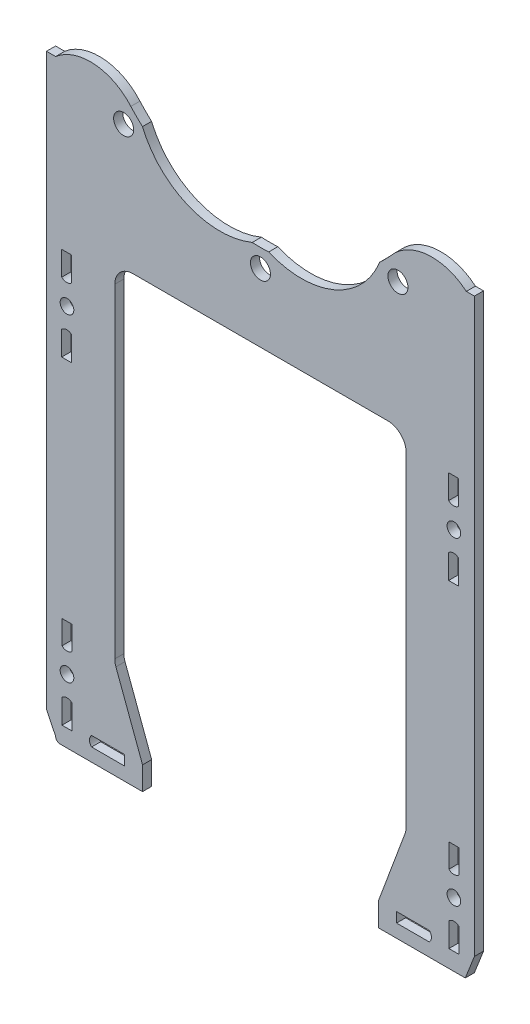
SolidWorks part; units mm, degrees
ref_plane "前视基准面" through (0, 0, 0) normal (0, 0, 1) x (1, 0, 0)
ref_plane "上视基准面" through (0, 0, 0) normal (0, 1, 0) x (1, 0, 0)
ref_plane "右视基准面" through (0, 0, 0) normal (1, 0, 0) x (0, 0, -1)
sketch "草图3" plane through (0, 0, 0) normal (0, 0, 1) x (1, 0, 0)
  line L0 (-37, -95.9902) -> (-37, -96.0902) construction
  line L5 (-37, -93.9902) -> (-30, -93.9902) construction
  line L6 (-37, -93.9902) -> (-37, -95.9902) construction
  line L7 (-37, -95.9902) -> (-30, -95.9902) construction
  line L8 (-30, -93.9902) -> (-30, -95.9902) construction
  line L9 (-37, -96.0902) -> (-37.1, -96.0902) construction
  line L12 (-42.5, -14.9402) -> (-41.8015, -14.9402) construction
  line L19 (-37.1, -96.0902) -> (-29.9, -96.0902)
  line L21 (-37.1, -93.8902) -> (-29.9, -93.8902)
  line L22 (-29.9, -96.0902) -> (-29.9, -93.8902)
  line L119 (-41.4551, -19.8902) -> (-41.4551, -25.1902)
  line L120 (-41.4551, -25.1902) -> (-43.6551, -25.1902)
  line L121 (-43.6551, -25.1902) -> (-43.6551, -19.8902)
  line L122 (-47, 31.3171) -> (-47, -93.8902)
  line L124 (37.1, -93.8902) -> (29.9, -93.8902)
  line L136 (37.1, -96.0902) -> (29.9, -96.0902)
  line L147 (30, -93.9902) -> (30, -95.9902) construction
  line L148 (29.9, -96.0902) -> (29.9, -93.8902)
  line L153 (37, -96.0902) -> (37.1, -96.0902) construction
  line L154 (37, -93.9902) -> (37, -95.9902) construction
  line L155 (37, -95.9902) -> (37, -96.0902) construction
  line L157 (43.5449, -25.1902) -> (43.5449, -19.8902)
  line L158 (41.3449, -25.1902) -> (43.5449, -25.1902)
  line L159 (41.3449, -19.8902) -> (41.3449, -25.1902)
  line L171 (-25.9, -97.9902) -> (-25.9, -93.8902)
  line L180 (0, 10.5098) -> (0, 13.5) construction
  line L187 (25.9, -97.9902) -> (25.9, -93.8902)
  line L195 (-25.9, -97.9902) -> (-25.9, -98.9902)
  line L196 (-25.9, -98.9902) -> (-45, -98.9902) construction
  line L197 (-45, -98.9902) -> (-45, -97.9902) construction
  line L198 (25.9, -97.9902) -> (25.9, -98.9902)
  line L199 (25.9, -98.9902) -> (45, -98.9902)
  line L209 (41.3449, -9.9902) -> (41.3449, -4.6902)
  line L210 (-44, -98.9902) -> (-25.9, -98.9902)
  line L212 (0, 56) -> (31.7001, 27.6918) construction
  line L213 (0, 56) -> (28.5728, 24.6019) construction
  line L218 (-45, 31.3171) -> (-47, 31.3171)
  line L220 (-47, -93.8902) -> (-45, -97.9902)
  line L221 (45.23, 31.7412) -> (47, 31.7412)
  line L223 (47, -93.8902) -> (45, -98.9902)
  line L224 (47, 31.7412) -> (47, -93.8902)
  line L225 (-31.7488, -78.175) -> (-25.9, -93.8902)
  line L227 (43.6, -80.0902) -> (41.4, -74.8902) construction
  line L228 (43.6, -74.8902) -> (41.4, -80.0902) construction
  line L229 (42.5, -79.9902) -> (42.5, -74.9902) construction
  line L230 (43.6, -80.0902) -> (43.6, -89.8902) construction
  line L231 (43.6, -95.1902) -> (43.6, -89.8902)
  line L232 (41.4, -95.1902) -> (43.6, -95.1902)
  line L233 (41.4, -89.8902) -> (41.4, -95.1902)
  line L234 (41.4, -74.8902) -> (41.4, -80.0902)
  line L235 (43.6, -74.8902) -> (43.6, -80.0902)
  line L236 (43.6, -74.8902) -> (41.4, -74.8902)
  line L237 (42.5, -79.9902) -> (42.5, -89.8902) construction
  line L239 (-41.4, -80.0902) -> (-43.6, -74.8902) construction
  line L240 (-41.4, -74.8902) -> (-43.6, -80.0902) construction
  line L241 (-42.5, -79.9902) -> (-42.5, -74.9902) construction
  line L242 (-41.4, -80.0902) -> (-41.4, -89.8902) construction
  line L243 (-41.4, -95.1902) -> (-41.4, -89.8902)
  line L244 (-43.6, -95.1902) -> (-41.4, -95.1902)
  line L245 (-43.6, -89.8902) -> (-43.6, -95.1902)
  line L246 (-43.6, -74.8902) -> (-43.6, -80.0902)
  line L247 (-41.4, -74.8902) -> (-41.4, -80.0902)
  line L248 (-41.4, -74.8902) -> (-43.6, -74.8902)
  line L249 (-42.5, -79.9902) -> (-42.5, -89.8902) construction
  line L258 (-28, -1.5) -> (28, -1.5)
  line L259 (-42.5, -14.9402) -> (42.5, -14.9402) construction
  line L260 (41.3449, -4.6902) -> (43.5449, -4.6902)
  line L261 (43.5449, -4.6902) -> (43.5449, -9.9902)
  line L262 (-43.6551, -4.6902) -> (-43.6551, -9.9902)
  line L263 (-41.4551, -4.6902) -> (-43.6551, -4.6902)
  line L264 (-41.4551, -9.9902) -> (-41.4551, -4.6902)
  line L267 (-32, -5.5) -> (-32, -76.7798)
  line L269 (32, -5.5) -> (32, -76.7798)
  line L270 (25.9, -93.8902) -> (31.7488, -78.175)
  arc A14 (-43.6551, -19.8902) -> (-41.4551, -19.8902) centre (-42.5551, -20.9902) cw
  arc A15 (41.3449, -19.8902) -> (43.5449, -19.8902) centre (42.4449, -20.9902) cw
  circle A17 centre (0, 13.5) radius 2.2
  circle A18 centre (-30.052, 25.948) radius 2.2
  circle A24 centre (30.2, 26.0826) radius 2.2
  arc A29 (37.1, -93.8902) -> (37.1, -96.0902) centre (36, -94.9902) cw
  arc A30 (-37.1, -96.0902) -> (-37.1, -93.8902) centre (-36, -94.9902) cw
  circle A40 centre (42.5, -14.9402) radius 1.5
  circle A41 centre (-42.5, -14.9402) radius 1.5
  arc A43 (-25.9127, 27.5258) -> (-1.8098, 17.5426) centre (-8.8696, 34.5856) ccw
  arc A44 (1.8098, 17.5426) -> (26.1792, 27.7706) centre (9.013, 34.5255) ccw
  arc A46 (-25.9127, 27.5258) -> (-28.4742, 30.0873) centre (0, 56) cw
  arc A47 (-1.8098, 17.5426) -> (1.8098, 17.5426) centre (0, 56) ccw
  arc A50 (-44, -98.9902) -> (-45, -97.9902) centre (-44, -97.9902) cw
  circle A52 centre (0, 56) radius 38.5 construction
  circle A53 centre (0, 56) radius 42.5 construction
  arc A54 (26.1792, 27.7706) -> (28.7166, 30.3561) centre (0, 56) ccw
  arc A55 (28.7166, 30.3561) -> (45.23, 31.7412) centre (37.6658, 22.7919) cw
  arc A56 (-28.4742, 30.0873) -> (-45, 31.3171) centre (-37.352, 22.4393) ccw
  arc A58 (41.4, -89.8902) -> (43.6, -89.8902) centre (42.5, -90.9902) cw
  arc A59 (41.4, -80.0902) -> (43.6, -80.0902) centre (42.5, -78.9902) ccw
  circle A60 centre (42.5, -84.9402) radius 1.5
  arc A61 (-43.6, -89.8902) -> (-41.4, -89.8902) centre (-42.5, -90.9902) cw
  arc A62 (-43.6, -80.0902) -> (-41.4, -80.0902) centre (-42.5, -78.9902) ccw
  circle A63 centre (-42.5, -84.9402) radius 1.5
  arc A69 (41.3449, -9.9902) -> (43.5449, -9.9902) centre (42.4449, -8.8902) ccw
  arc A70 (-43.6551, -9.9902) -> (-41.4551, -9.9902) centre (-42.5551, -8.8902) ccw
  arc A72 (32, -76.7798) -> (31.7488, -78.175) centre (28, -76.7798) cw
  arc A73 (-32, -76.7798) -> (-31.7488, -78.175) centre (-28, -76.7798) ccw
  arc A74 (32, -5.5) -> (28, -1.5) centre (28, -5.5) ccw
  arc A75 (-32, -5.5) -> (-28, -1.5) centre (-28, -5.5) cw
  point P64 (32, -77.5)
  point P67 (-32, -77.5)
  point P75 (32, -1.5)
  point P79 (-32, -1.5)
  point P128 (42.5, -77.4902)
  point P145 (-42.5, -77.4902)
  dimension "D1" = 1
  dimension "D2" = 125.2073
  dimension "D9" = 4
  dimension "D3" = 94
  dimension "D4" = 15
  dimension "D5" = 15
  dimension "D6" = 15
  dimension "D7" = 76
  dimension "D8" = 76
extrude "凸台-拉伸1" add sketch "草图3" along normal blind 2
